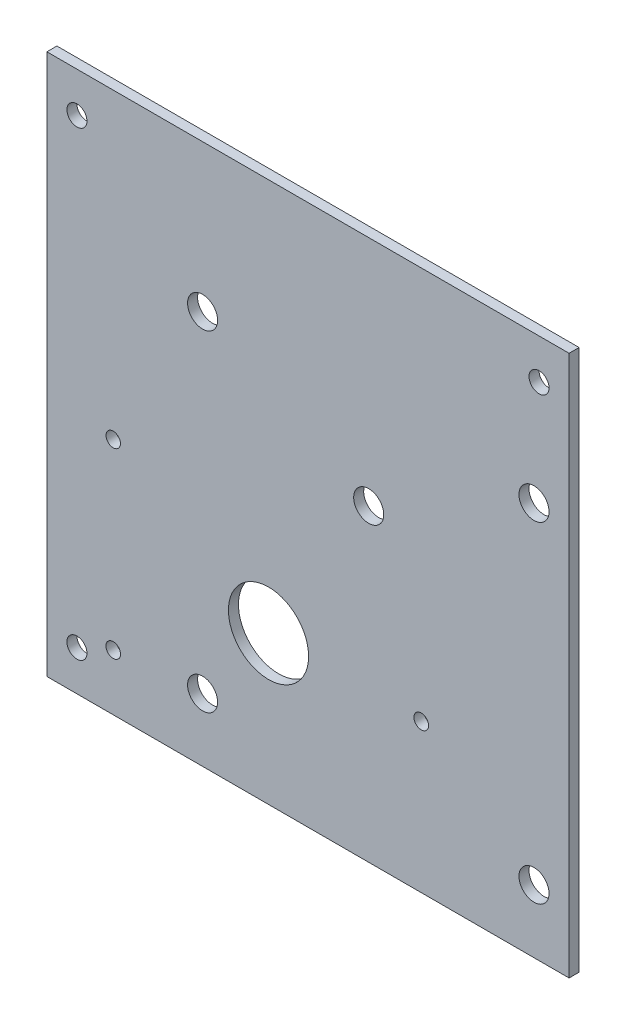
SolidWorks part; units mm, degrees
ref_plane "Front Plane" through (0, 0, 0) normal (0, 0, 1) x (1, 0, 0)
ref_plane "Top Plane" through (0, 0, 0) normal (0, 1, 0) x (1, 0, 0)
ref_plane "Right Plane" through (0, 0, 0) normal (1, 0, 0) x (0, 0, -1)
sketch "Sketch1" plane through (0, 0, 0) normal (0, 0, 1) x (1, 0, 0)
  line L1 (0, 0) -> (165.481, 0)
  line L2 (0, 0) -> (0, 171.45)
  line L3 (0, 171.45) -> (165.481, 171.45)
  line L4 (165.481, 0) -> (165.481, 171.45)
  circle A0 centre (21.0185, 17.78) radius 2.3178
  circle A1 centre (21.0185, 75.565) radius 2.286
  circle A2 centre (118.6307, 46.99) radius 2.3177
  circle A3 centre (70.231, 46.99) radius 12.7
  circle A4 centre (101.981, 97.79) radius 4.7625
  circle A5 centre (49.3395, 20.0025) radius 4.7625
  circle A6 centre (49.3395, 124.7775) radius 4.7625
  circle A7 centre (154.3685, 20.0025) radius 4.7625
  circle A8 centre (154.3685, 124.7775) radius 4.7625
  dimension "D3" = 4.6355
  dimension "D6" = 4.572
  dimension "D9" = 4.6355
  dimension "D12" = 25.4
  dimension "D13" = 9.525
  dimension "D18" = 9.525
  dimension "D21" = 9.525
  dimension "D24" = 9.525
  dimension "D25" = 9.525
  dimension "D1" = 171.45
  dimension "D2" = 165.481
  dimension "D4" = 17.78
  dimension "D5" = 21.0185
  dimension "D7" = 21.0185
  dimension "D8" = 75.565
  dimension "D10" = 118.6307
  dimension "D11" = 46.99
  dimension "D14" = 70.231
  dimension "D15" = 46.99
  dimension "D16" = 101.981
  dimension "D17" = 97.79
  dimension "D19" = 20.0025
  dimension "D20" = 49.3395
  dimension "D22" = 49.3395
  dimension "D23" = 124.7775
  dimension "D26" = 20.0025
  dimension "D27" = 154.3685
  dimension "D28" = 124.7775
  dimension "D29" = 154.3685
extrude "Boss-Extrude1" add sketch "Sketch1" along normal blind 3.175
sketch "Sketch2" plane through (0, 0, 3.175) normal (0, 0, 1) x (1, 0, 0)
  line L0 (165.481, 171.45) -> (0, 171.45) construction
  line L1 (0, 171.45) -> (0, 0) construction
  line L2 (165.481, 0) -> (165.481, 171.45) construction
  circle A0 centre (9.525, 158.75) radius 3.175
  circle A1 centre (9.525, 12.7) radius 3.175
  circle A2 centre (155.956, 158.75) radius 3.175
  dimension "D1" = 6.35
  dimension "D2" = 12.7
  dimension "D3" = 9.525
  dimension "D4" = 6.35
  dimension "D5" = 158.75
  dimension "D6" = 9.525
  dimension "D7" = 6.35
  dimension "D8" = 9.525
  dimension "D9" = 12.7
extrude "Cut-Extrude1" cut sketch "Sketch2" against normal up to surface (3.175 mm away) up to face at (159.131, 20.0025, 0)
